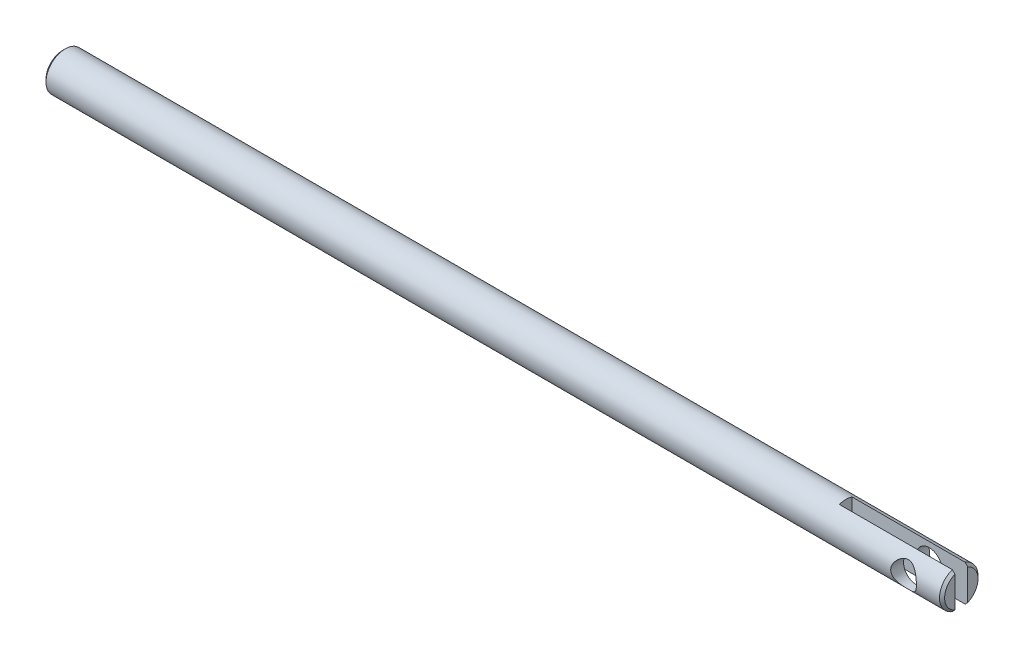
SolidWorks part; units mm, degrees
ref_plane "Front Plane" through (0, 0, 0) normal (0, 0, 1) x (1, 0, 0)
ref_plane "Top Plane" through (0, 0, 0) normal (0, 1, 0) x (1, 0, 0)
ref_plane "Right Plane" through (0, 0, 0) normal (1, 0, 0) x (0, 0, -1)
sketch "Sketch1" plane through (0, 0, 0) normal (0, 0, 1) x (1, 0, 0)
  line L0 (0, 0) -> (-70, 0) construction
  line L1 (-70, 0) -> (-70, 1.5)
  line L2 (-70, 1.5) -> (0, 1.5)
  line L3 (0, 1.5) -> (0, 0.5)
  line L6 (-9, 0) -> (-70, 0)
  line L7 (-9, 0) -> (0, 0)
  line L8 (0, 0) -> (0, 0.5)
  dimension "D1" = 3
  dimension "D4" = 70
  dimension "D5" = 1.5
  dimension "D6" = 1
revolve "Revolve1" add sketch "Sketch1" angle 360 about L0
sketch "Sketch2" plane through (0, 0, 0) normal (0, 0, 1) x (1, 0, 0)
  circle A0 centre (-3, 0) radius 1
  dimension "D1" = 2
  dimension "D2" = 3
extrude "Cut-Extrude1" cut sketch "Sketch2" against normal through all both and the other way through all
chamfer "Chamfer1" distance 0.2 angle 45 2 edges at (-70, 1.5, 0) (0, 1.5, 0)
sketch "Sketch3" plane through (0, 0, 0) normal (0, 1, 0) x (1, 0, 0)
  line L0 (0, -1.3) -> (0, 1.3) construction
  line L1 (0, 0.5) -> (-9, 0.5)
  line L2 (0, 0.5) -> (0, -0.5)
  line L3 (0, -0.5) -> (-9, -0.5)
  line L4 (-9, 0.5) -> (-9, -0.5)
  point P6 (-9, 0)
  dimension "D1" = 1
  dimension "D2" = 9
extrude "Cut-Extrude2" cut sketch "Sketch3" against normal through all both and the other way through all
